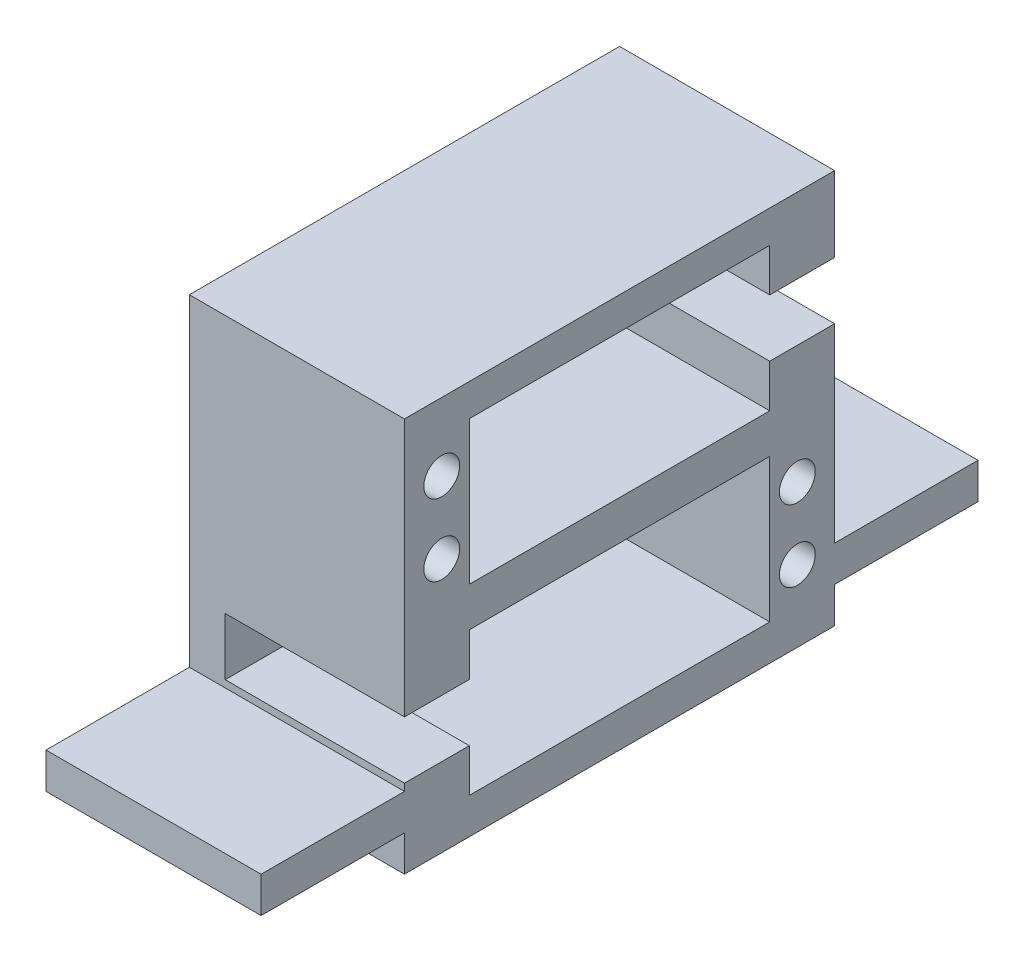
SolidWorks part; units mm, degrees
ref_plane "Front Plane" through (0, 0, 0) normal (0, 0, 1) x (1, 0, 0)
ref_plane "Top Plane" through (0, 0, 0) normal (0, 1, 0) x (1, 0, 0)
ref_plane "Right Plane" through (0, 0, 0) normal (1, 0, 0) x (0, 0, -1)
sketch "Sketch1" plane through (0, 0, 0) normal (0, 1, 0) x (1, 0, 0)
  line L1 (-0.874, 37.3622) -> (42.126, 37.3622)
  line L2 (-0.874, 37.3622) -> (-0.874, -22.6378)
  line L3 (-0.874, -22.6378) -> (42.126, -22.6378)
  line L4 (42.126, 37.3622) -> (42.126, -22.6378)
  dimension "D1" = 60
  dimension "D2" = 43
extrude "Boss-Extrude1" add sketch "Sketch1" along normal blind 55
sketch "Sketch2" plane through (42.126, 0, 0) normal (1, 0, 0) x (0, 0, -1)
  line L0 (-22.6378, 55) -> (37.3622, 55) construction
  line L1 (-13.5878, 50.5) -> (28.3122, 50.5)
  line L2 (-13.5878, 50.5) -> (-13.5878, 30.5)
  line L3 (-13.5878, 30.5) -> (28.3122, 30.5)
  line L4 (28.3122, 50.5) -> (28.3122, 30.5)
  line L5 (-22.6378, 55) -> (-22.6378, 0) construction
  line L6 (37.3622, 55) -> (37.3622, 0) construction
  line L8 (-13.5878, 25) -> (28.3122, 25)
  line L9 (-13.5878, 25) -> (-13.5878, 5)
  line L10 (-13.5878, 5) -> (28.3122, 5)
  line L11 (28.3122, 25) -> (28.3122, 5)
  dimension "D1" = 4.5
  dimension "D2" = 9.05
  dimension "D3" = 9.05
  dimension "D4" = 5.5
  dimension "D5" = 20
  dimension "D6" = 20
  dimension "D7" = 9.05
  dimension "9" = 9.05
extrude "Cut-Extrude1" cut sketch "Sketch2" against normal blind 38
sketch "Sketch3" plane through (42.126, 0, 0) normal (1, 0, 0) x (0, 0, -1)
  line L0 (-22.6378, 55) -> (-22.6378, 0) construction
  line L1 (-22.6378, 19) -> (-13.5878, 19)
  line L2 (-22.6378, 19) -> (-22.6378, 11)
  line L3 (-22.6378, 11) -> (-13.5878, 11)
  line L4 (-13.5878, 19) -> (-13.5878, 11)
  line L5 (-13.5878, 25) -> (-13.5878, 5) construction
  line L6 (-13.5878, 5) -> (28.3122, 5) construction
  line L7 (28.3122, 30.5) -> (28.3122, 50.5) construction
  line L8 (28.3122, 44.5) -> (37.3622, 44.5)
  line L9 (28.3122, 44.5) -> (28.3122, 36.5)
  line L10 (28.3122, 36.5) -> (37.3622, 36.5)
  line L11 (37.3622, 44.5) -> (37.3622, 36.5)
  line L12 (37.3622, 55) -> (37.3622, 0) construction
  line L13 (-13.5878, 30.5) -> (28.3122, 30.5) construction
  dimension "D1" = 6
  dimension "D2" = 8
  dimension "D3" = 6
  dimension "D4" = 8
extrude "Cut-Extrude2" cut sketch "Sketch3" against normal blind 38
sketch "Sketch4" plane through (42.126, 0, 0) normal (1, 0, 0) x (0, 0, -1)
  line L0 (23.65, 0) -> (-23.65, 0) construction
  line L1 (-22.6378, 55) -> (37.3622, 55)
  line L2 (-22.6378, 55) -> (-22.6378, 0)
  line L3 (-22.6378, 0) -> (37.3622, 0)
  line L4 (37.3622, 55) -> (37.3622, 0)
  line L5 (37.3622, 36.5) -> (37.3622, 0) construction
extrude "Cut-Extrude3" cut sketch "Sketch4" against normal blind 13
sketch "Sketch11" plane through (0, 0, 22.6378) normal (0, 0, 1) x (1, 0, 0)
  line L0 (-0.874, 55) -> (-0.874, 0) construction
  line L1 (-0.874, 10) -> (29.126, 10)
  line L2 (-0.874, 10) -> (-0.874, 5)
  line L3 (-0.874, 5) -> (29.126, 5)
  line L4 (29.126, 10) -> (29.126, 5)
  line L5 (-0.874, 55) -> (29.126, 55) construction
  dimension "D1" = 30
  dimension "5" = 5
  dimension "D3" = 45
extrude "Boss-Extrude5" add sketch "Sketch11" along normal blind 20 and the other way blind 80
sketch "Sketch12" plane through (29.126, 0, 0) normal (1, 0, 0) x (0, 0, -1)
  line L0 (-13.5878, 30.5) -> (-13.5878, 50.5) construction
  line L1 (28.3122, 50.5) -> (-13.5878, 50.5) construction
  line L2 (-13.5878, 50.5) -> (-13.5878, 30.5) construction
  circle A0 centre (-17.4378, 45.5) radius 2.5
  circle A1 centre (-17.4378, 35.5) radius 2.5
  dimension "D1" = 3.85
  dimension "D2" = 5
  dimension "D3" = 5
  dimension "D5" = 3.85
  dimension "D6" = 5
  dimension "D4" = 10
extrude "Cut-Extrude4" cut sketch "Sketch12" against normal blind 10
sketch "Sketch13" plane through (29.126, 0, 0) normal (1, 0, 0) x (0, 0, -1)
  line L0 (28.3122, 10) -> (28.3122, 25) construction
  line L1 (28.3122, 25) -> (-13.5878, 25) construction
  line L2 (28.3122, 25) -> (28.3122, 10) construction
  circle A0 centre (32.1622, 20) radius 2.5
  circle A1 centre (32.1622, 10) radius 2.5
  dimension "D1" = 3.85
  dimension "D2" = 5
  dimension "D3" = 5
  dimension "D4" = 10
  dimension "D5" = 3.85
  dimension "D6" = 5
extrude "Cut-Extrude5" cut sketch "Sketch13" against normal blind 10
sketch "Sketch15" plane through (29.126, 0, 0) normal (1, 0, 0) x (0, 0, -1)
  line L3 (-13.5878, 10) -> (28.3122, 10)
  line L4 (-13.5878, 10) -> (-13.5878, 5)
  line L5 (-13.5878, 5) -> (28.3122, 5)
  line L6 (28.3122, 10) -> (28.3122, 5)
  dimension "D1" = 5
extrude "Cut-Extrude7" cut sketch "Sketch15" against normal up to surface (25 mm away)
